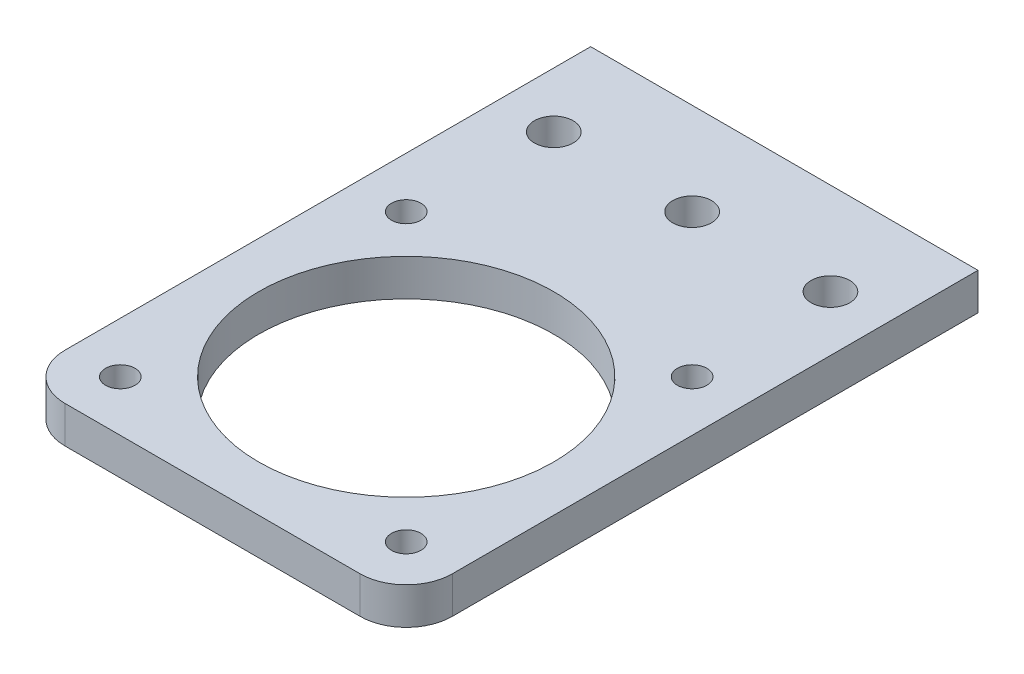
SolidWorks part; units mm, degrees
ref_plane "前视基准面" through (0, 0, 0) normal (0, 0, 1) x (1, 0, 0)
ref_plane "上视基准面" through (0, 0, 0) normal (0, 1, 0) x (1, 0, 0)
ref_plane "右视基准面" through (0, 0, 0) normal (1, 0, 0) x (0, 0, -1)
other "Configuration Table"
sketch "草图1" plane through (0, 0, 0) normal (0, 1, 0) x (1, 0, 0)
  line L0 (0, -20) -> (42, -20) construction
  line L1 (0, 0) -> (42, 0)
  line L2 (0, 0) -> (0, -57)
  line L3 (5, -62) -> (37, -62)
  line L4 (42, 0) -> (42, -57)
  circle A0 centre (5.5, -25.5) radius 1.6
  circle A1 centre (36.5, -25.5) radius 1.6
  circle A2 centre (36.5, -56.5) radius 1.6
  circle A3 centre (5.5, -56.5) radius 1.6
  arc A4 (37, -62) -> (42, -57) centre (37, -57) ccw
  arc A5 (0, -57) -> (5, -62) centre (5, -57) ccw
  circle A6 centre (21, -41) radius 16
  circle A7 centre (21, -10) radius 2.1
  circle A8 centre (36, -10) radius 2.1
  circle A9 centre (6, -10) radius 2.1
  point P7 (21, -41)
  point P19 (21, -41)
  point P21 (0, -62)
  dimension "D6" = 3.2
  dimension "D10" = 5
  dimension "D11" = 32
  dimension "D12" = 4.2
  dimension "D13" = 4.2
  dimension "D14" = 4.2
  dimension "D1" = 42
  dimension "D2" = 62
  dimension "D3" = 42
  dimension "D4" = 21
  dimension "D5" = 21
  dimension "D7" = 15.5
  dimension "D8" = 15.5
  dimension "D15" = 15
  dimension "D16" = 15
  dimension "D17" = 10
  dimension "D9" = 4
extrude "凸台-拉伸1" add sketch "草图1" along normal blind 4
